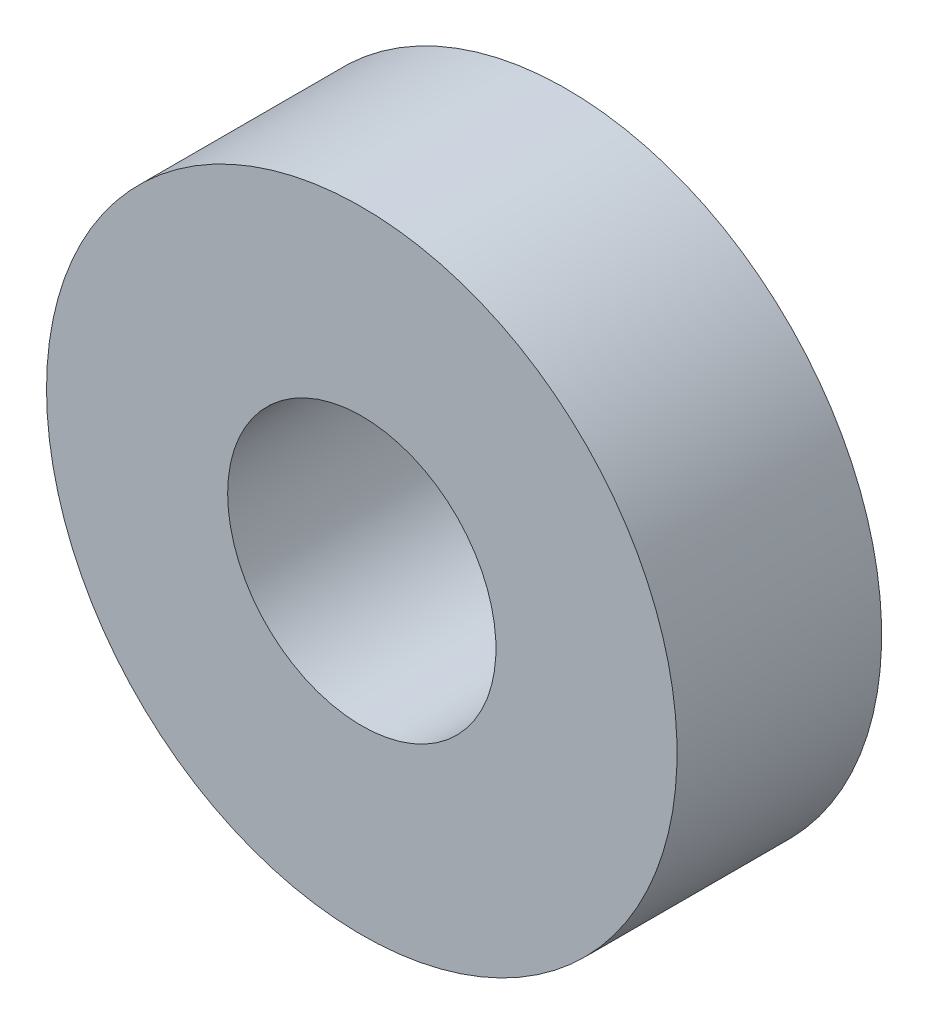
SolidWorks part; units mm, degrees
ref_plane "Front Plane" through (0, 0, 0) normal (0, 0, 1) x (1, 0, 0)
ref_plane "Top Plane" through (0, 0, 0) normal (0, 1, 0) x (1, 0, 0)
ref_plane "Right Plane" through (0, 0, 0) normal (1, 0, 0) x (0, 0, -1)
sketch "Sketch1" plane through (0, 0, 0) normal (0, 0, 1) x (1, 0, 0)
  circle A0 centre (0, 0) radius 23.5
  circle A1 centre (0, 0) radius 10
  dimension "D1" = 47
  dimension "D2" = 20
extrude "Boss-Extrude1" add sketch "Sketch1" along normal blind 15.25
